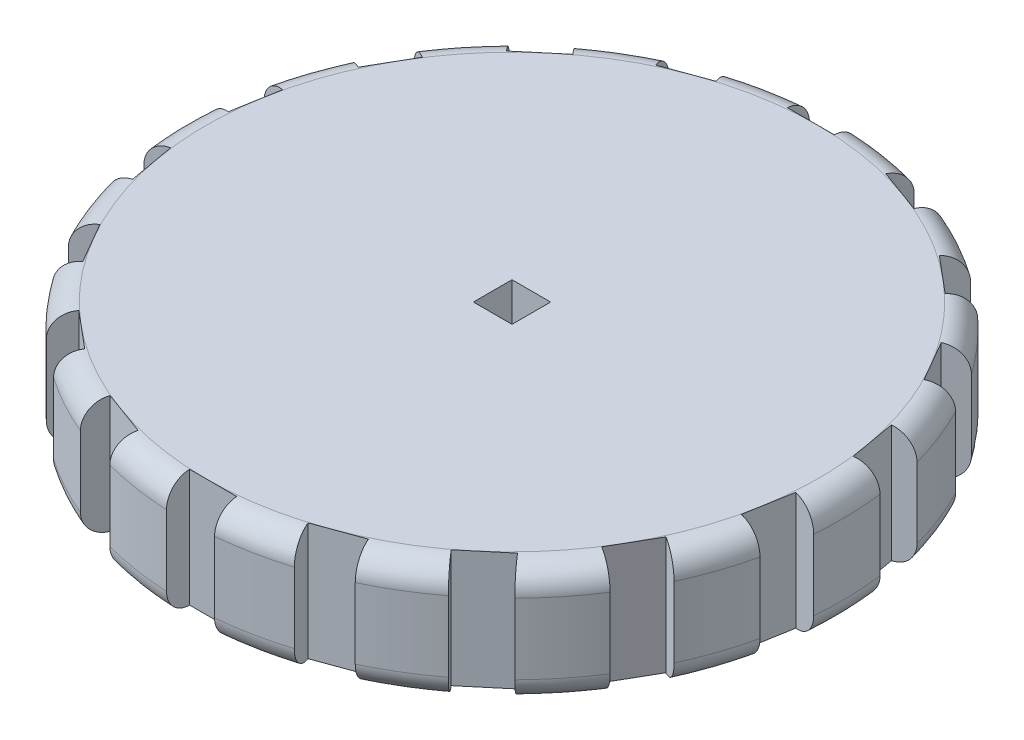
SolidWorks part; units mm, degrees
ref_plane "前视基准面" through (0, 0, 0) normal (0, 0, 1) x (1, 0, 0)
ref_plane "上视基准面" through (0, 0, 0) normal (0, 1, 0) x (1, 0, 0)
ref_plane "右视基准面" through (0, 0, 0) normal (1, 0, 0) x (0, 0, -1)
sketch "草图1" plane through (0, 0, 0) normal (0, 1, 0) x (1, 0, 0)
  line L1 (-27.9247, -7.2133) -> (-28.9247, -7.2133)
  line L2 (-27.9247, -7.2133) -> (-27.9247, -5.2133)
  line L3 (-27.9247, -5.2133) -> (-28.9247, -5.2133)
  line L4 (-28.9247, -7.2133) -> (-28.9247, -5.2133)
  circle A0 centre (-28.5698, 1.7867) radius 7
  dimension "D1" = 14
  dimension "D2" = 1
  dimension "D3" = 2
  dimension "D4" = 7
extrude "凸台-拉伸1" add sketch "草图1" along normal blind 2.5 contours A0
sketch "草图2" plane through (0, 2.5, 0) normal (0, 1, 0) x (1, 0, 0)
  line L1 (-28.9798, 2.1967) -> (-28.1598, 2.1967)
  line L2 (-28.9798, 2.1967) -> (-28.9798, 1.3767)
  line L3 (-28.9798, 1.3767) -> (-28.1598, 1.3767)
  line L4 (-28.1598, 2.1967) -> (-28.1598, 1.3767)
  line L5 (-28.9798, 2.1967) -> (-28.1598, 1.3767) construction
  line L6 (-28.9798, 1.3767) -> (-28.1598, 2.1967) construction
  point P0 (-28.5698, 1.7867)
  dimension "D1" = 0.82
sketch "草图3" plane through (0, 0, 0) normal (0, -1, 0) x (1, 0, 0)
  circle A0 centre (-28.5698, -1.7867) radius 2
extrude "凸台-拉伸3" add sketch "草图3" along normal blind 1.5
fillet "圆角2" radius 0.5 2 edges at (-28.5698, 0, 5.2133) (-28.5698, 2.5, 5.2133)
sketch "草图4" plane through (0, 2.5, 0) normal (0, 1, 0) x (1, 0, 0)
  line L0 (-22.0698, 1.7867) -> (-35.0698, 1.7867) construction
  line L1 (-28.9177, -4.7133) -> (-27.9177, -4.7133)
  line L2 (-28.9177, -4.7133) -> (-28.9177, -6.2133)
  line L3 (-28.9177, -6.2133) -> (-27.9177, -6.2133)
  line L4 (-27.9177, -4.7133) -> (-27.9177, -6.2133)
  line L5 (-35.0698, 1.7867) -> (-28.5698, 8.2867) construction
  line L6 (-28.5698, 8.2867) -> (-28.5698, -4.7133) construction
  line L7 (-31.1199, -4.2023) -> (-31.6329, -5.6118)
  line L8 (-31.1199, -4.2023) -> (-30.1802, -4.5443)
  line L9 (-30.1802, -4.5443) -> (-30.6932, -5.9539)
  line L10 (-31.6329, -5.6118) -> (-30.6932, -5.9539)
  line L11 (-33.0145, -2.9689) -> (-33.9786, -4.118)
  line L12 (-33.0145, -2.9689) -> (-32.2484, -3.6117)
  line L13 (-32.2484, -3.6117) -> (-33.2126, -4.7608)
  line L14 (-33.9786, -4.118) -> (-33.2126, -4.7608)
  line L15 (-34.3729, -1.162) -> (-35.672, -1.912)
  line L16 (-34.3729, -1.162) -> (-33.8729, -2.028)
  line L17 (-33.8729, -2.028) -> (-35.172, -2.778)
  line L18 (-35.672, -1.912) -> (-35.172, -2.778)
  line L19 (-35.0315, 1.0006) -> (-36.5087, 0.7401)
  line L20 (-35.0315, 1.0006) -> (-34.8579, 0.0158)
  line L21 (-34.8579, 0.0158) -> (-36.3351, -0.2447)
  line L22 (-36.5087, 0.7401) -> (-36.3351, -0.2447)
  line L23 (-34.9107, 3.258) -> (-36.3879, 3.5185)
  line L24 (-34.9107, 3.258) -> (-35.0843, 2.2732)
  line L25 (-35.0843, 2.2732) -> (-36.5615, 2.5337)
  line L26 (-36.3879, 3.5185) -> (-36.5615, 2.5337)
  line L27 (-34.0251, 5.338) -> (-35.3241, 6.088)
  line L28 (-34.0251, 5.338) -> (-34.5251, 4.472)
  line L29 (-34.5251, 4.472) -> (-35.8241, 5.222)
  line L30 (-35.3241, 6.088) -> (-35.8241, 5.222)
  line L31 (-32.4815, 6.9896) -> (-33.4456, 8.1387)
  line L32 (-32.4815, 6.9896) -> (-33.2475, 6.3468)
  line L33 (-33.2475, 6.3468) -> (-34.2117, 7.4959)
  line L34 (-33.4456, 8.1387) -> (-34.2117, 7.4959)
  line L35 (-30.4661, 8.0137) -> (-30.9791, 9.4232)
  line L36 (-30.4661, 8.0137) -> (-31.4057, 7.6717)
  line L37 (-31.4057, 7.6717) -> (-31.9188, 9.0812)
  line L38 (-30.9791, 9.4232) -> (-31.9188, 9.0812)
  line L39 (-28.2219, 8.2867) -> (-28.2219, 9.7867)
  line L40 (-28.2219, 8.2867) -> (-29.2219, 8.2867)
  line L41 (-29.2219, 8.2867) -> (-29.2219, 9.7867)
  line L42 (-28.2219, 9.7867) -> (-29.2219, 9.7867)
  line L43 (-26.0198, 7.7757) -> (-25.5068, 9.1853)
  line L44 (-26.0198, 7.7757) -> (-26.9595, 8.1178)
  line L45 (-26.9595, 8.1178) -> (-26.4465, 9.5273)
  line L46 (-25.5068, 9.1853) -> (-26.4465, 9.5273)
  line L47 (-24.1252, 6.5424) -> (-23.161, 7.6915)
  line L48 (-24.1252, 6.5424) -> (-24.8913, 7.1852)
  line L49 (-24.8913, 7.1852) -> (-23.9271, 8.3342)
  line L50 (-23.161, 7.6915) -> (-23.9271, 8.3342)
  line L51 (-22.7667, 4.7354) -> (-21.4677, 5.4854)
  line L52 (-22.7667, 4.7354) -> (-23.2667, 5.6015)
  line L53 (-23.2667, 5.6015) -> (-21.9677, 6.3515)
  line L54 (-21.4677, 5.4854) -> (-21.9677, 6.3515)
  line L55 (-22.1082, 2.5728) -> (-20.631, 2.8333)
  line L56 (-22.1082, 2.5728) -> (-22.2818, 3.5576)
  line L57 (-22.2818, 3.5576) -> (-20.8046, 3.8181)
  line L58 (-20.631, 2.8333) -> (-20.8046, 3.8181)
  line L59 (-22.229, 0.3154) -> (-20.7518, 0.0549)
  line L60 (-22.229, 0.3154) -> (-22.0554, 1.3002)
  line L61 (-22.0554, 1.3002) -> (-20.5781, 1.0397)
  line L62 (-20.7518, 0.0549) -> (-20.5781, 1.0397)
  line L63 (-23.1146, -1.7646) -> (-21.8156, -2.5146)
  line L64 (-23.1146, -1.7646) -> (-22.6146, -0.8985)
  line L65 (-22.6146, -0.8985) -> (-21.3156, -1.6485)
  line L66 (-21.8156, -2.5146) -> (-21.3156, -1.6485)
  line L67 (-24.6582, -3.4162) -> (-23.694, -4.5653)
  line L68 (-24.6582, -3.4162) -> (-23.8922, -2.7734)
  line L69 (-23.8922, -2.7734) -> (-22.928, -3.9225)
  line L70 (-23.694, -4.5653) -> (-22.928, -3.9225)
  line L71 (-26.6736, -4.4403) -> (-26.1606, -5.8498)
  line L72 (-26.6736, -4.4403) -> (-25.7339, -4.0983)
  line L73 (-25.7339, -4.0983) -> (-25.2209, -5.5078)
  line L74 (-26.1606, -5.8498) -> (-25.2209, -5.5078)
  circle A0 centre (-28.5698, 1.7867) radius 6.5 construction
  point P13 (-28.4177, -4.7133)
  point P14 (-28.5698, 1.7867)
  point P83 (-28.5698, 1.7867)
  dimension "D1" = 1.5
  dimension "D2" = 1
  dimension "D3" = 6.5
  dimension "D4" = 18
extrude "切除-拉伸1" cut sketch "草图4" against normal blind 10
extrude "切除-拉伸2" cut sketch "草图2" against normal blind 2.5
